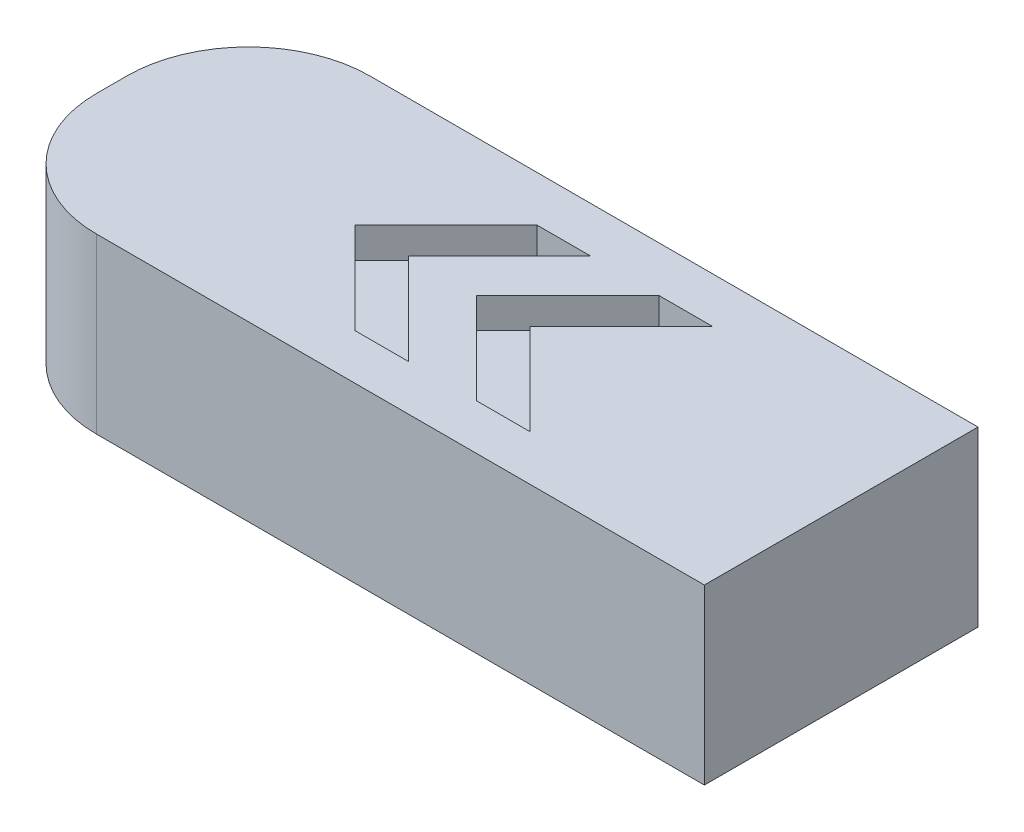
SolidWorks part; units mm, degrees
ref_plane "Front Plane" through (0, 0, 0) normal (0, 0, 1) x (1, 0, 0)
ref_plane "Top Plane" through (0, 0, 0) normal (0, 1, 0) x (1, 0, 0)
ref_plane "Right Plane" through (0, 0, 0) normal (1, 0, 0) x (0, 0, -1)
sketch "Sketch1" plane through (0, 0, 0) normal (0, 1, 0) x (1, 0, 0)
  line L1 (0, 0) -> (24, 0)
  line L2 (0, 0) -> (0, 9)
  line L3 (0, 9) -> (24, 9)
  line L4 (24, 0) -> (24, 9)
  dimension "D1" = 24
  dimension "D2" = 9
extrude "Boss-Extrude1" add sketch "Sketch1" along normal blind 5.7
fillet "Fillet1" radius 4 1 edges at (0, 2.85, 0)
fillet "Fillet2" radius 4 1 edges at (0, 2.85, -9)
sketch "Sketch2" plane through (0, 5.7, 0) normal (0, 1, 0) x (1, 0, 0)
  line L0 (12.7678, 1.5) -> (11, 1.5)
  line L1 (11, 1.5) -> (8, 4.5)
  line L2 (8, 4.5) -> (11, 7.5)
  line L3 (11, 7.5) -> (12.7678, 7.5)
  line L4 (12.7678, 7.5) -> (9.7678, 4.5)
  line L5 (9.7678, 4.5) -> (12.7678, 1.5)
  line L6 (4, 0) -> (24, 0) construction
  line L7 (24, 9) -> (4, 9) construction
  line L8 (0, 5) -> (0, 4) construction
  dimension "D1" = 1.5
  dimension "D2" = 1.5
  dimension "D3" = 8
  dimension "D4" = 1.25
  dimension "D5" = 1.25
  dimension "D6" = 4.5
  dimension "D7" = 4.5
extrude "Cut-Extrude2" cut sketch "Sketch2" against normal blind 1
pattern_linear "LPattern1" count 2 spacing 4 along (1, 0, 0) of "Cut-Extrude2"
